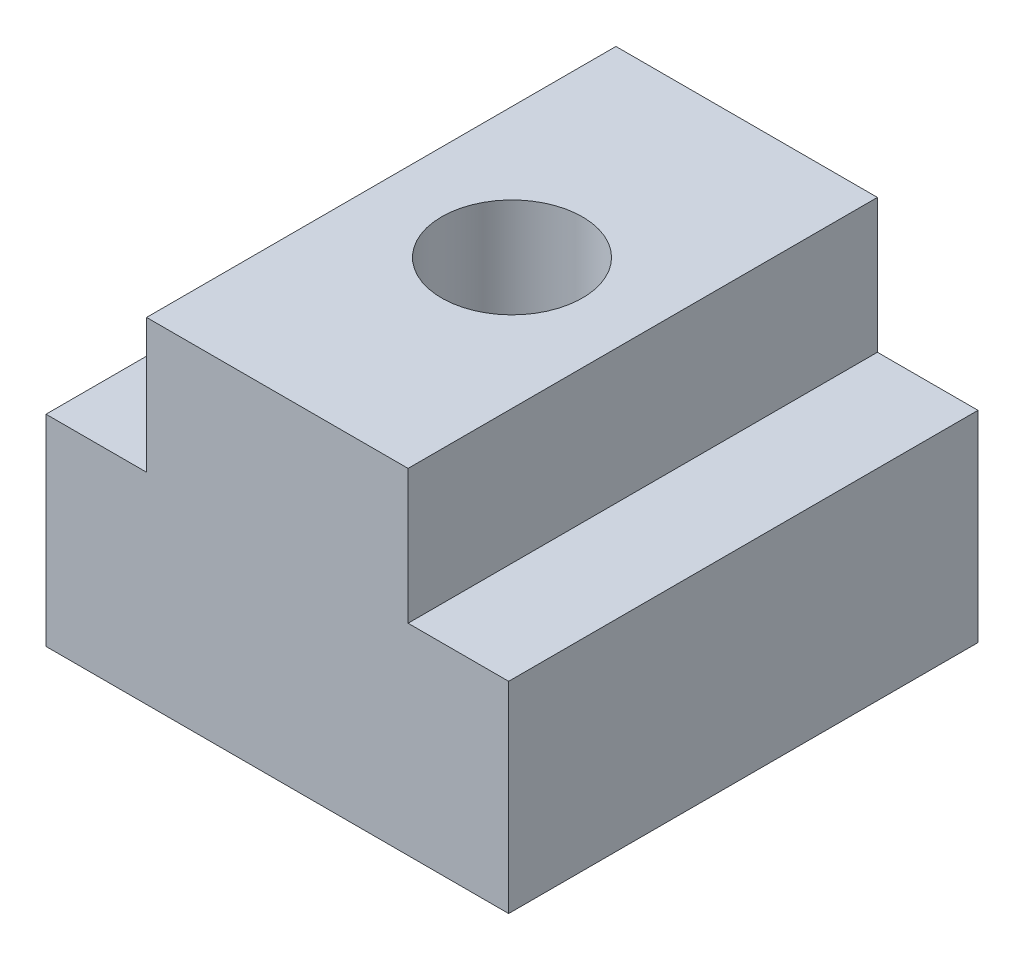
SolidWorks part; units mm, degrees
ref_plane "Front" through (0, 0, 0) normal (0, 0, 1) x (1, 0, 0)
ref_plane "Top" through (0, 0, 0) normal (0, 1, 0) x (1, 0, 0)
ref_plane "Right" through (0, 0, 0) normal (1, 0, 0) x (0, 0, -1)
sketch "Esquisse1" plane through (0, 0, 0) normal (0, 0, 1) x (1, 0, 0)
  line L1 (0, 0) -> (13.8, 0)
  line L2 (0, 0) -> (0, 6)
  line L3 (0, 6) -> (13.8, 6)
  line L4 (13.8, 0) -> (13.8, 6)
  dimension "D1" = 13.8
  dimension "D2" = 6
extrude "Boss.-Extru.1" add sketch "Esquisse1" along normal blind 14
sketch "Esquisse2" plane through (0, 0, 14) normal (0, 0, 1) x (1, 0, 0)
  line L0 (13.8, 6) -> (0, 6) construction
  line L1 (3, 6) -> (10.8, 6)
  line L2 (3, 6) -> (3, 10)
  line L3 (3, 10) -> (10.8, 10)
  line L4 (10.8, 6) -> (10.8, 10)
  line L5 (6.9, 10) -> (6.9, 6) construction
  line L6 (0, 0) -> (13.8, 0) construction
  dimension "D1" = 7.8
  dimension "D2" = 10
extrude "Boss.-Extru.2" add sketch "Esquisse2" against normal up to vertex (14 mm away) up to point (13.8, 6, 0)
sketch "Esquisse3" plane through (0, 10, 0) normal (0, 1, 0) x (1, 0, 0)
  line L0 (6.9, 0) -> (6.9, -14) construction
  line L1 (10.8, 0) -> (3, 0) construction
  line L2 (10.8, -14) -> (3, -14) construction
  circle A0 centre (6.9, -7) radius 2.1
  dimension "D1" = 4.2
extrude "Enlèv. mat.-Extru.1" cut sketch "Esquisse3" against normal through all
